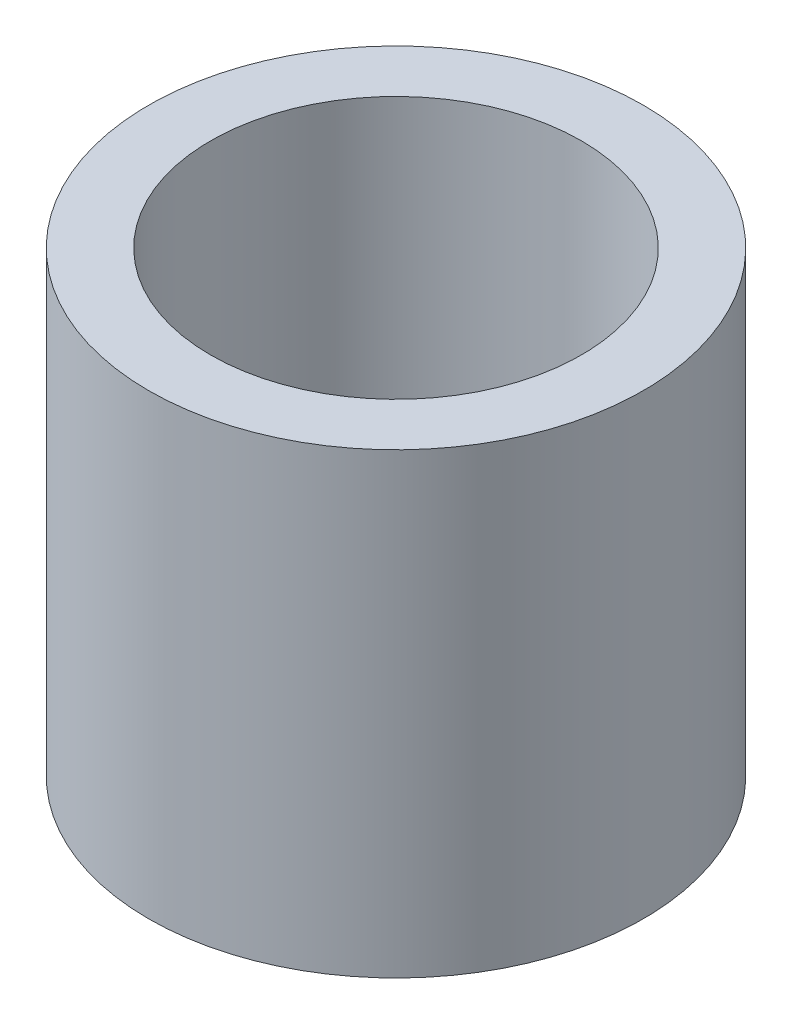
SolidWorks part; units mm, degrees
ref_plane "Front" through (0, 0, 0) normal (0, 0, 1) x (1, 0, 0)
ref_plane "Top" through (0, 0, 0) normal (0, 1, 0) x (1, 0, 0)
ref_plane "Right" through (0, 0, 0) normal (1, 0, 0) x (0, 0, -1)
sketch "Sketch1" plane through (0, 0, 0) normal (0, 1, 0) x (1, 0, 0)
  line L0 (0, 3) -> (0, -2.5)
  line L1 (0, -2.5) -> (-1.6583, -2.5)
  line L2 (-1.6583, -2.5) -> (1.6583, -2.5)
  circle A0 centre (0, 0) radius 3
  circle A1 centre (0, 0) radius 4
extrude "Boss-Extrude1" add sketch "Sketch1" along normal blind 7.399 contours A1 A0
